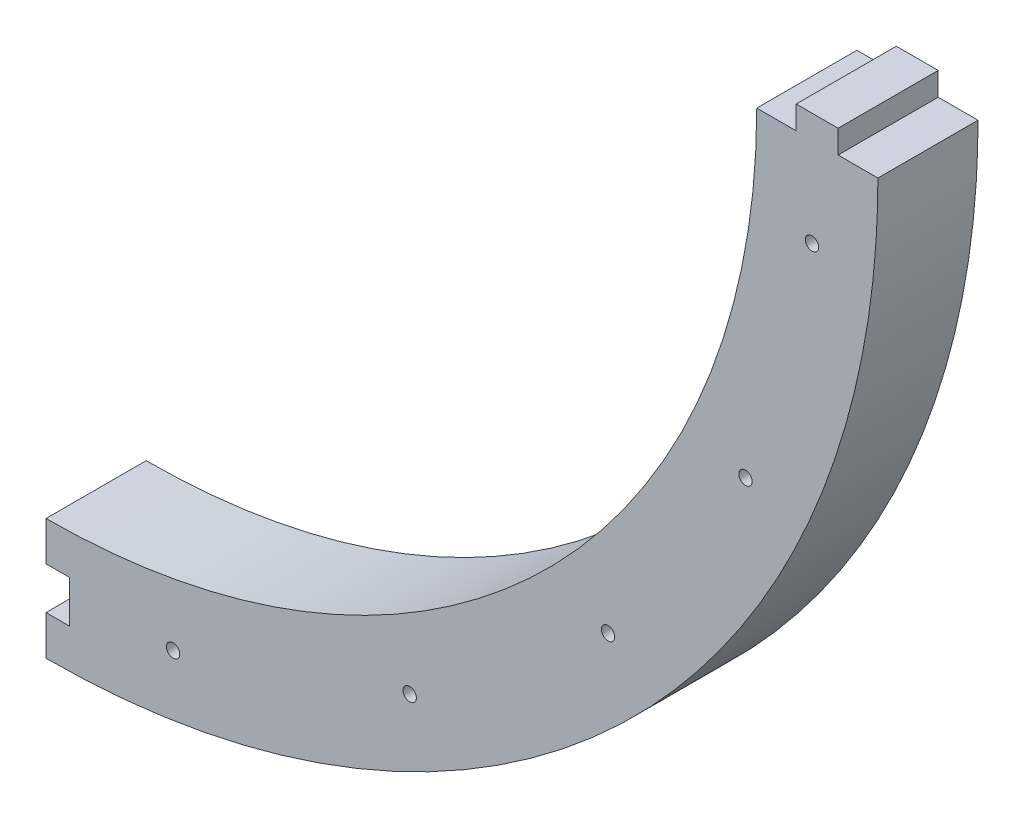
SolidWorks part; units mm, degrees
ref_plane "Front Plane" through (0, 0, 0) normal (0, 0, 1) x (1, 0, 0)
ref_plane "Top Plane" through (0, 0, 0) normal (0, 1, 0) x (1, 0, 0)
ref_plane "Right Plane" through (0, 0, 0) normal (1, 0, 0) x (0, 0, -1)
sketch "Model" plane through (0, 0, 0) normal (0, 0, 1) x (1, 0, 0)
  line L0 (152.2311, -4.3296) -> (152.2311, -8.7482)
  line L1 (152.2311, -8.7482) -> (144.7342, -8.7482)
  line L2 (9.5049, -143.9828) -> (9.5049, -151.4555)
  line L3 (9.5049, -151.4555) -> (13.9477, -151.4555)
  line L4 (13.9477, -151.4555) -> (13.9477, -159.4767)
  line L5 (13.9477, -159.4767) -> (9.5049, -159.4767)
  line L6 (9.5049, -159.4767) -> (9.5049, -167.0197)
  line L7 (167.7754, -8.7482) -> (160.2071, -8.7482)
  line L8 (160.2071, -8.7482) -> (160.2071, -4.3296)
  line L9 (160.2071, -4.3296) -> (152.2311, -4.3296)
  spline S0 degree 3 poles (144.7342, -8.7482) (144.693, -83.4174) (84.1736, -143.9392) (9.5049, -143.9828) knots 2 2 2 2 3 3 3 3
  spline S1 degree 3 poles (9.5049, -167.0197) (96.9153, -167.0197) (167.7754, -96.1592) (167.7754, -8.7482) knots 8 8 8 8 9 9 9 9
extrude "Boss-Extrude1" add sketch "Model" along normal blind 19.05 contours S0 L2 L3 L4 L5 L6 S1 L7 L8 L9 L0 L1
sketch "Sketch2" plane through (0, 0, 19.05) normal (0, 0, 1) x (1, 0, 0)
  line L0 (13.9477, -151.4555) -> (13.9477, -159.4767) construction
  line L1 (152.2311, -4.3296) -> (160.2071, -4.3296) construction
  line L2 (13.9477, -155.4661) -> (10.7358, -155.4661) construction
  line L3 (156.2191, -4.3296) -> (156.2191, -1.2797) construction
  line L4 (9.6394, -9.0579) -> (116.4432, -109.4182) construction
  line L5 (9.6394, -9.0579) -> (78.6959, -138.3268) construction
  line L6 (9.6394, -9.0579) -> (116.4432, -109.4182) construction
  line L7 (9.6394, -9.0579) -> (142.5863, -70.7374) construction
  arc A0 (156.2191, -4.3296) -> (13.9477, -155.4661) centre (9.7143, -8.9496) cw construction
  circle A1 centre (116.4432, -109.4182) radius 1.27
  circle A2 centre (78.6959, -138.3268) radius 1.27
  circle A3 centre (33.6808, -153.6305) radius 1.27
  circle A4 centre (142.5863, -70.7374) radius 1.27
  circle A5 centre (155.2383, -25.7974) radius 1.27
  dimension "D1" = 3
  dimension "D2" = 18.67
  dimension "D3" = 146.558
  dimension "D5" = 18.33
  dimension "D6" = 146.558
  dimension "D4" = 3
extrude "Cut-Extrude1" cut sketch "Sketch2" against normal blind 19.05
